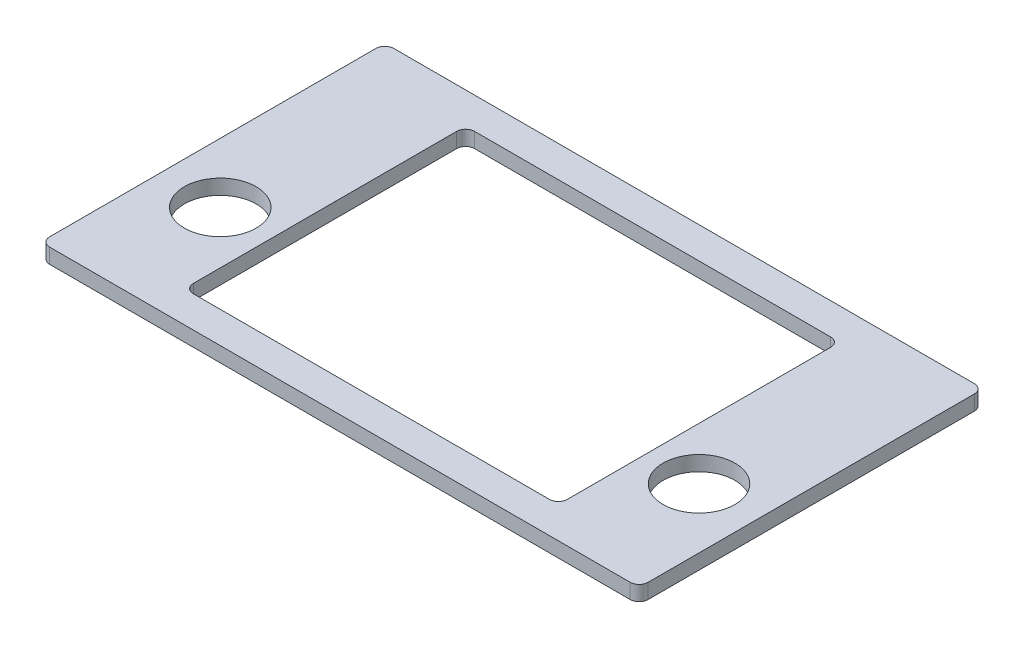
SolidWorks part; units mm, degrees
ref_plane "Front Plane" through (0, 0, 0) normal (0, 0, 1) x (1, 0, 0)
ref_plane "Top Plane" through (0, 0, 0) normal (0, 1, 0) x (1, 0, 0)
ref_plane "Right Plane" through (0, 0, 0) normal (1, 0, 0) x (0, 0, -1)
sketch "Sketch1" plane through (0, 0, 0) normal (0, 1, 0) x (1, 0, 0)
  line L1 (3.81, 0) -> (250.19, 0)
  line L2 (0, 3.81) -> (0, 142.24)
  line L3 (3.81, 146.05) -> (250.19, 146.05)
  line L4 (254, 3.81) -> (254, 142.24)
  line L5 (51.435, 132.715) -> (202.565, 132.715)
  line L6 (47.625, 128.905) -> (47.625, 17.145)
  line L7 (51.435, 13.335) -> (202.565, 13.335)
  line L8 (206.375, 128.905) -> (206.375, 17.145)
  arc A0 (250.19, 0) -> (254, 3.81) centre (250.19, 3.81) ccw
  arc A1 (250.19, 146.05) -> (254, 142.24) centre (250.19, 142.24) cw
  arc A2 (0, 142.24) -> (3.81, 146.05) centre (3.81, 142.24) cw
  arc A3 (3.81, 0) -> (0, 3.81) centre (3.81, 3.81) cw
  arc A4 (47.625, 17.145) -> (51.435, 13.335) centre (51.435, 17.145) ccw
  arc A5 (202.565, 13.335) -> (206.375, 17.145) centre (202.565, 17.145) ccw
  arc A6 (202.565, 132.715) -> (206.375, 128.905) centre (202.565, 128.905) cw
  arc A7 (51.435, 132.715) -> (47.625, 128.905) centre (51.435, 128.905) ccw
  point P11 (254, 0)
  point P14 (254, 146.05)
  point P17 (0, 146.05)
  point P20 (0, 0)
  point P25 (206.375, 13.335)
  point P28 (206.375, 132.715)
  point P31 (47.625, 132.715)
  dimension "D7" = 3.81
  dimension "D1" = 254
  dimension "D2" = 146.05
  dimension "D3" = 119.38
  dimension "D4" = 158.75
  dimension "D5" = 13.335
  dimension "D6" = 47.625
extrude "Boss-Extrude1" add sketch "Sketch1" along normal blind 6.35
sketch "Sketch2" plane through (0, 6.35, 0) normal (0, 1, 0) x (1, 0, 0)
  line L0 (3.81, 0) -> (250.19, 0) construction
  line L1 (0, 142.24) -> (0, 3.81) construction
  line L2 (254, 3.81) -> (254, 142.24) construction
  circle A0 centre (25.4, 50.8) radius 15.24
  circle A1 centre (228.6, 50.8) radius 15.24
  dimension "D1" = 30.48
  dimension "D2" = 30.48
  dimension "D3" = 50.8
  dimension "D4" = 50.8
  dimension "D5" = 25.4
  dimension "D6" = 25.4
extrude "Cut-Extrude1" cut sketch "Sketch2" against normal through all
equation "\"D5@Sketch1\"=(\"D2@Sketch1\"-\"D3@Sketch1\")/2"
equation "\"D6@Sketch1\"=(\"D1@Sketch1\"-\"D4@Sketch1\")/2"
